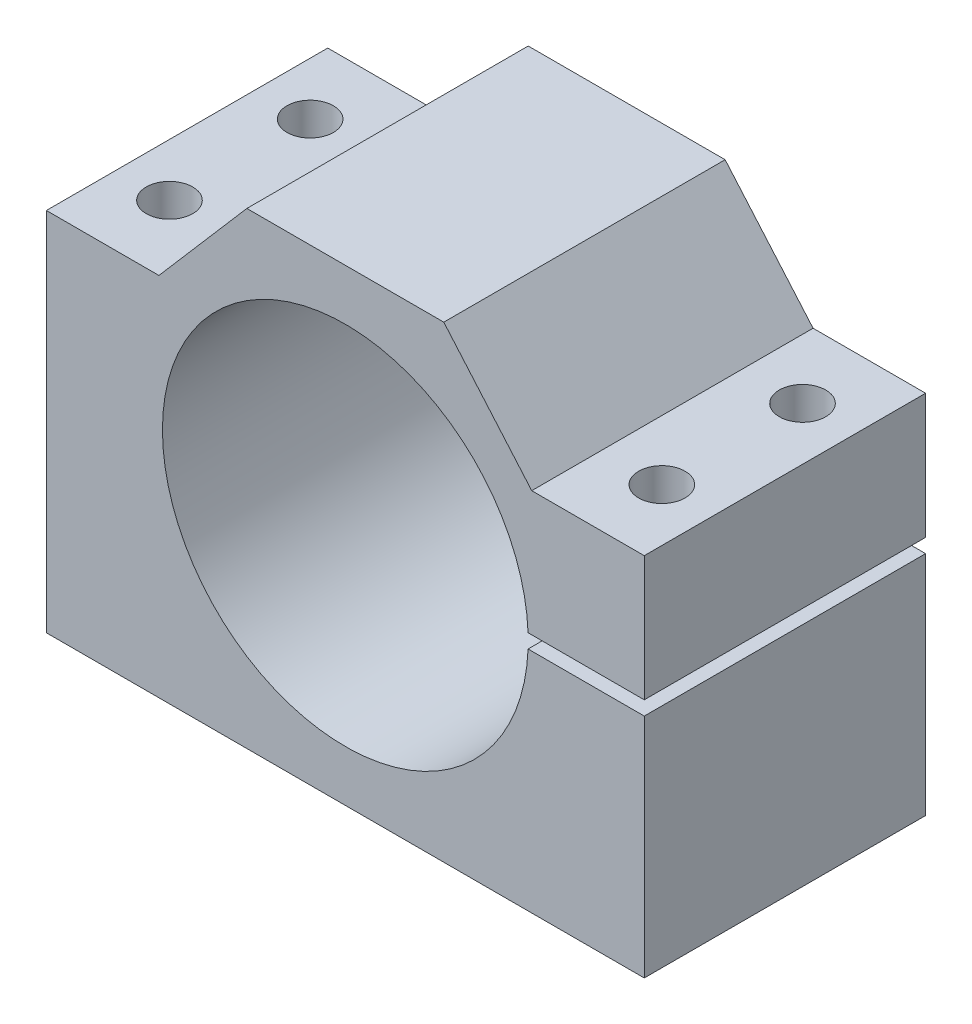
SolidWorks part; units mm, degrees
ref_plane "Plan de face" through (0, 0, 0) normal (0, 0, 1) x (1, 0, 0)
ref_plane "Plan de dessus" through (0, 0, 0) normal (0, 1, 0) x (1, 0, 0)
ref_plane "Plan de droite" through (0, 0, 0) normal (1, 0, 0) x (0, 0, -1)
sketch "Esquisse1" plane through (0, 0, 0) normal (0, 0, 1) x (1, 0, 0)
  line L0 (-165.7741, -1.4935) -> (-80.7741, -1.4935)
  line L1 (-80.7741, -1.4935) -> (-80.7741, 50.5065)
  line L2 (-80.7741, 50.5065) -> (-96.7741, 50.5065)
  line L3 (-96.7741, 50.5065) -> (-109.2741, 65.0065)
  line L4 (-109.2741, 65.0065) -> (-137.2741, 65.0065)
  line L5 (-137.2741, 65.0065) -> (-149.7741, 50.5065)
  line L6 (-149.7741, 50.5065) -> (-165.7741, 50.5065)
  line L7 (-165.7741, 50.5065) -> (-165.7741, -1.4935)
  line L8 (-123.2741, 65.0065) -> (-123.2741, -1.4935) construction
  circle A0 centre (-123.2741, 31.7565) radius 26
  point P2 (-123.2741, 65.0065)
  point P9 (-123.2741, -1.4935)
  point P10 (-123.2741, 31.7565)
  dimension "D1" = 52
  dimension "D2" = 52
  dimension "D3" = 14.5
  dimension "D4" = 85
  dimension "D5" = 28
  dimension "D6" = 16
extrude "Boss.-Extru.1" add sketch "Esquisse1" along normal blind 40
sketch "Esquisse2" plane through (0, 0, 40) normal (0, 0, 1) x (1, 0, 0)
  line L0 (-80.7741, -1.4935) -> (-80.7741, 50.5065) construction
  line L1 (-97.2934, 32.7565) -> (-80.7741, 32.7565)
  line L3 (-97.2934, 30.7565) -> (-80.7741, 30.7565)
  line L4 (-80.7741, 32.7565) -> (-80.7741, 30.7565)
  circle A0 centre (-123.2741, 31.7565) radius 26 construction
  circle A1 centre (-123.2741, 31.7565) radius 26 construction
  arc A2 (-97.2934, 30.7565) -> (-97.2934, 32.7565) centre (-123.2741, 31.7565) ccw
  point P9 (-80.7741, 31.7565)
  dimension "D1" = 2
extrude "Enlèv. mat.-Extru.1" cut sketch "Esquisse2" against normal up to next
sketch "Esquisse3" plane through (0, 50.5065, 0) normal (0, 1, 0) x (1, 0, 0)
  line L0 (-158.2741, -10) -> (-158.2741, -30) construction
  line L1 (-165.7741, -40) -> (-165.7741, 0) construction
  line L2 (-158.2741, -30) -> (-88.2741, -30) construction
  line L3 (-109.2741, -40) -> (-137.2741, -40) construction
  circle A0 centre (-158.2741, -10) radius 3.3
  circle A1 centre (-158.2741, -30) radius 3.3
  circle A2 centre (-88.2741, -10) radius 3.3
  circle A3 centre (-88.2741, -30) radius 3.3
  point P8 (-158.2741, -20)
  point P11 (-165.7741, -20)
  point P12 (-123.2741, -30)
  point P15 (-123.2741, -40)
  dimension "D3" = 6.6
  dimension "D1" = 20
  dimension "D2" = 70
extrude "Enlèv. mat.-Extru.2" cut sketch "Esquisse3" against normal through all
